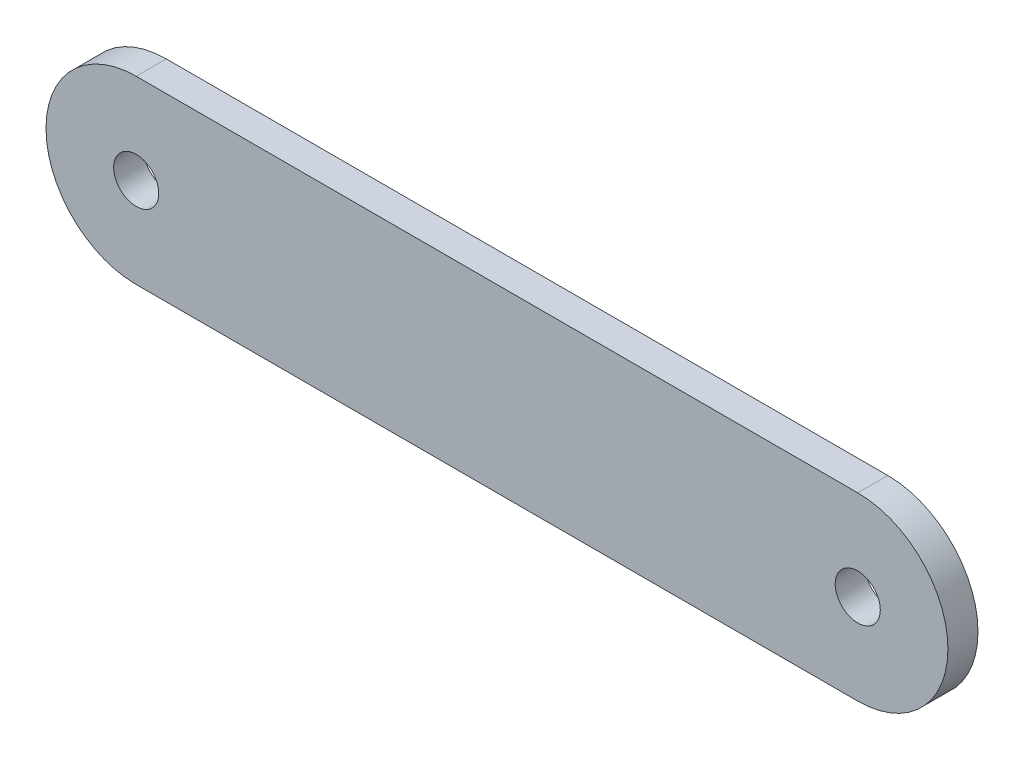
SolidWorks part; units mm, degrees
ref_plane "Front Plane" through (0, 0, 0) normal (0, 0, 1) x (1, 0, 0)
ref_plane "Top Plane" through (0, 0, 0) normal (0, 1, 0) x (1, 0, 0)
ref_plane "Right Plane" through (0, 0, 0) normal (1, 0, 0) x (0, 0, -1)
sketch "Sketch1" plane through (0, 0, 0) normal (0, 0, 1) x (1, 0, 0)
  line L0 (0, 0) -> (152.4, 0) construction
  line L1 (0, 19.05) -> (152.4, 19.05)
  line L2 (0, -19.05) -> (152.4, -19.05)
  arc A0 (0, 19.05) -> (0, -19.05) centre (0, 0) ccw
  arc A1 (152.4, -19.05) -> (152.4, 19.05) centre (152.4, 0) ccw
  circle A2 centre (0, 0) radius 4.7625
  circle A3 centre (152.4, 0) radius 4.7625
  point P3 (76.2, 0)
  point P12 (0, 0)
  point P13 (0, 0)
  dimension "D2" = 9.525
  dimension "D3" = 9.525
  dimension "D1" = 152.4
  dimension "D4" = 38.1
extrude "Boss-Extrude1" add sketch "Sketch1" along normal blind 6.35
equation "\"Center to Center length\"= 6"
equation "\"Depth of part\"= .25"
equation "\"Hole Dia\"= 3 / 8"
equation "\"D1@Sketch1\"=\"Center to Center length\""
equation "\"D2@Sketch1\"=\"Hole Dia\""
equation "\"D3@Sketch1\"=\"D2@Sketch1\""
equation "\"D1@Boss-Extrude1\"=\"Depth of part\""
